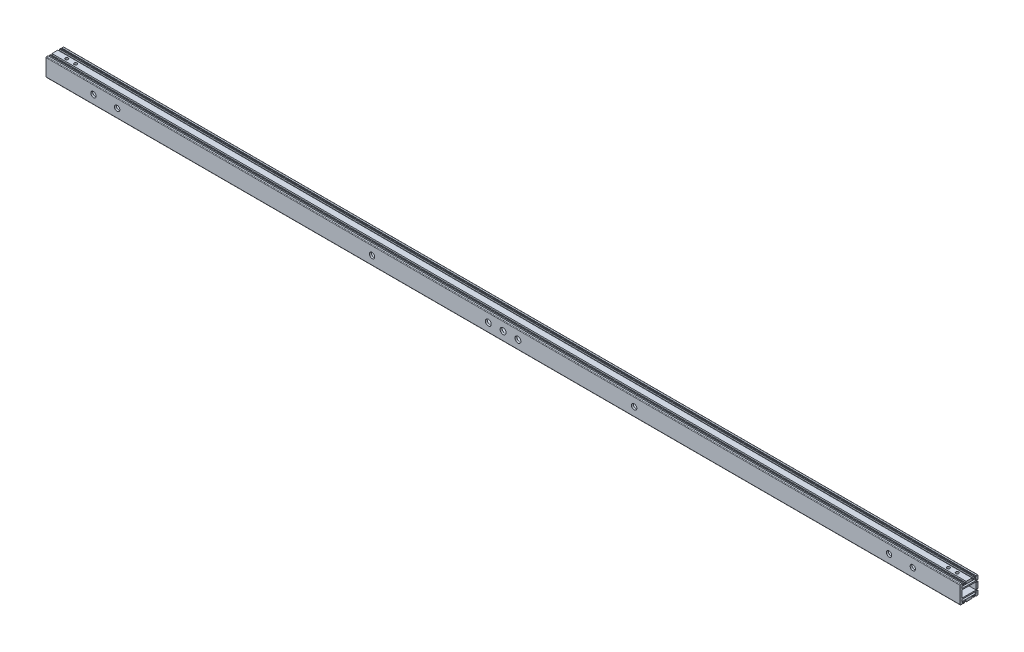
SolidWorks part; units mm, degrees
ref_plane "前视基准面" through (0, 0, 0) normal (0, 0, 1) x (1, 0, 0)
ref_plane "上视基准面" through (0, 0, 0) normal (0, 1, 0) x (1, 0, 0)
ref_plane "右视基准面" through (0, 0, 0) normal (1, 0, 0) x (0, 0, -1)
sketch "草图1" plane through (0, 0, 0) normal (1, 0, 0) x (0, 0, -1)
  line L0 (-15, 15) -> (15, -15) construction
  line L1 (-14, 15) -> (-11.5, 15)
  line L2 (-15, 14) -> (-15, -14)
  line L3 (-14, -15) -> (-11.5, -15)
  line L4 (15, 14) -> (15, 8)
  line L5 (15, 15) -> (-15, -15) construction
  line L6 (-11.5, 15) -> (-11.5, 13.5)
  line L7 (-11.5, 13.5) -> (-11.4, 13.5)
  line L8 (-11, 13.1) -> (-11, 12)
  line L9 (-11, 12) -> (-9.5, 12)
  line L10 (-9.5, 12) -> (-9.5, 15)
  line L11 (-9.5, 15) -> (-8, 15)
  line L12 (-8, 15) -> (-8, 12.5)
  line L13 (-8, 12.5) -> (-5, 12.5)
  line L14 (-5, 12.5) -> (-5, 15)
  line L15 (-5, 15) -> (5, 15)
  line L16 (0, 21.5201) -> (0, -18.309) construction
  line L17 (0, 55) -> (0, -55) construction
  line L18 (5, 12.5) -> (5, 15)
  line L19 (8, 12.5) -> (5, 12.5)
  line L20 (8, 15) -> (8, 12.5)
  line L21 (9.5, 15) -> (8, 15)
  line L22 (9.5, 12) -> (9.5, 15)
  line L23 (11, 12) -> (9.5, 12)
  line L24 (11, 13.1) -> (11, 12)
  line L25 (11.5, 13.5) -> (11.4, 13.5)
  line L26 (11.5, 15) -> (11.5, 13.5)
  line L27 (8, 15) -> (9.5, 15)
  line L28 (11.5, 15) -> (14, 15)
  line L29 (-19.8303, 0) -> (22.13, 0) construction
  line L30 (55, 0) -> (-55, 0) construction
  line L31 (8, -15) -> (9.5, -15)
  line L32 (11.5, -15) -> (11.5, -13.5)
  line L33 (11.5, -13.5) -> (11.4, -13.5)
  line L34 (11, -13.1) -> (11, -12)
  line L35 (11, -12) -> (9.5, -12)
  line L36 (9.5, -12) -> (9.5, -15)
  line L37 (9.5, -15) -> (8, -15)
  line L38 (8, -15) -> (8, -12.5)
  line L39 (8, -12.5) -> (5, -12.5)
  line L40 (5, -12.5) -> (5, -15)
  line L41 (-5, -15) -> (5, -15)
  line L42 (-5, -12.5) -> (-5, -15)
  line L43 (-8, -12.5) -> (-5, -12.5)
  line L44 (-8, -15) -> (-8, -12.5)
  line L45 (-9.5, -15) -> (-8, -15)
  line L46 (-9.5, -12) -> (-9.5, -15)
  line L47 (-11, -12) -> (-9.5, -12)
  line L48 (-11, -13.1) -> (-11, -12)
  line L49 (-11.5, -13.5) -> (-11.4, -13.5)
  line L50 (-11.5, -15) -> (-11.5, -13.5)
  line L51 (-9.5, -15) -> (-8, -15)
  line L52 (-5, -15) -> (5, -15)
  line L53 (8, -15) -> (9.5, -15)
  line L54 (11.5, -15) -> (14, -15)
  line L55 (15, 8) -> (12.5, 8)
  line L56 (12.5, 8) -> (12.5, 5)
  line L57 (12.5, 5) -> (15, 5)
  line L58 (12.5, -5) -> (15, -5)
  line L59 (12.5, -8) -> (12.5, -5)
  line L60 (15, -8) -> (12.5, -8)
  line L61 (15, 5) -> (15, -5)
  line L62 (15, -8) -> (15, -14)
  line L63 (12, -10.5) -> (12, -8.5)
  line L64 (-11.5, 11) -> (11.5, 11)
  line L65 (-12, 10.5) -> (-12, 8.5)
  line L66 (-11.5, 8) -> (11.5, 8)
  line L67 (12, 10.5) -> (12, 8.5)
  line L68 (-11.5, -8) -> (11.5, -8)
  line L69 (-12, -10.5) -> (-12, -8.5)
  line L70 (-11.5, -11) -> (11.5, -11)
  line L72 (-11.75, 6) -> (11.75, 6)
  line L73 (-11.75, 6) -> (-11.75, -6)
  line L74 (-11.75, -6) -> (11.75, -6)
  line L75 (11.75, 6) -> (11.75, -6)
  arc A0 (12, 8.5) -> (11.5, 8) centre (11.5, 8.5) cw
  arc A1 (11.5, 11) -> (12, 10.5) centre (11.5, 10.5) cw
  arc A2 (-11.5, 11) -> (-12, 10.5) centre (-11.5, 10.5) ccw
  arc A3 (-11.5, 8) -> (-12, 8.5) centre (-11.5, 8.5) cw
  arc A4 (-11, -13.1) -> (-11.4, -13.5) centre (-11.4, -13.1) cw
  arc A5 (11.4, -13.5) -> (11, -13.1) centre (11.4, -13.1) cw
  arc A6 (11.4, 13.5) -> (11, 13.1) centre (11.4, 13.1) ccw
  arc A7 (-11, 13.1) -> (-11.4, 13.5) centre (-11.4, 13.1) ccw
  arc A8 (-11.5, -8) -> (-12, -8.5) centre (-11.5, -8.5) ccw
  arc A9 (-11.5, -11) -> (-12, -10.5) centre (-11.5, -10.5) cw
  arc A10 (11.5, -11) -> (12, -10.5) centre (11.5, -10.5) ccw
  arc A11 (12, -8.5) -> (11.5, -8) centre (11.5, -8.5) ccw
  arc A12 (14, 15) -> (15, 14) centre (14, 14) cw
  arc A13 (14, -15) -> (15, -14) centre (14, -14) ccw
  arc A14 (-15, -14) -> (-14, -15) centre (-14, -14) ccw
  arc A15 (-15, 14) -> (-14, 15) centre (-14, 14) cw
  point P69 (12, 11)
  point P72 (-12, 11)
  point P77 (-11, -13.5)
  point P80 (11, -13.5)
  point P83 (11, 13.5)
  point P86 (-11, 13.5)
  point P99 (-12, -11)
  point P100 (12, -11)
  dimension "D17" = 0.5
  dimension "D18" = 0.4
  dimension "D21" = 1
  dimension "D1" = 3.5
  dimension "D2" = 1.5
  dimension "D3" = 0.5
  dimension "D4" = 1.5
  dimension "D5" = 3
  dimension "D6" = 30
  dimension "D7" = 30
  dimension "D8" = 1.5
  dimension "D9" = 2.5
  dimension "D10" = 3
  dimension "D11" = 2.5
  dimension "D12" = 7
  dimension "D13" = 3
  dimension "D14" = 4
  dimension "D15" = 3
  dimension "D16" = 24
  dimension "D19" = 23.5
  dimension "D20" = 12
extrude "凸台-拉伸1" add sketch "草图1" along normal mid plane 1542 contours A15 L2 A14 L3 L50 L49 A4 L48 L47 L46 L45 L44 L43 L42 L41 L40 L39 L38 L31 L36 L35 L34 A5 L33 L32 L54 A13 L62 L60 L59 L58 L61 L57 L56 L55 L4 A12 L28 L26 L25 A6 L24 L23 L22 L21 L20 L19 L18 L15 L14 L13
hole_wizard "M6 螺纹孔1" positions "草图3" profile "草图2" tap size "M6" standard "GB"
sketch "草图3" plane through (0, 0, -15) normal (0, 0, -1) x (-1, 0, 0)
  line L0 (771, 5) -> (771, -5) construction
  line L1 (-771, 15) -> (771, 15) construction
  line L3 (-771, -15) -> (771, -15) construction
  point P0 (751, 0)
  point P6 (736, 0)
  point P8 (-736, 0)
  point P11 (-751, 0)
  dimension "D1" = 20
  dimension "D2" = 15
  dimension "D3" = 15
  dimension "D4" = 15
sketch "草图2" plane through (-751, 0, -15) normal (1, 0, 0) x (0, 1, 0)
  line L0 (0, 0) -> (0, 16.5022)
  line L1 (0, 16.5022) -> (2.5, 15)
  line L2 (2.5, 15) -> (2.5, 0)
  line L5 (2.5, 0) -> (0, 0)
  line L10 (0, 16.5022) -> (-2.5, 15) construction
  line L11 (0, -6.35) -> (0, 107.95) construction
  dimension "螺纹孔钻头直径" = 5
  dimension "螺纹孔钻头深度" = 15
  dimension "导头角度" = 118
cosmetic thread "孔螺蚊线1" parameters "D1"=3.25, "D2"=6
cosmetic thread "孔螺蚊线2" parameters "D1"=3.25, "D2"=6
cosmetic thread "孔螺蚊线3" parameters "D1"=3.25, "D2"=6
cosmetic thread "孔螺蚊线4" parameters "D1"=3.25, "D2"=6
hole_wizard "M6 螺纹孔2" positions "草图5" profile "草图4" tap size "M6" standard "GB"
sketch "草图5" plane through (0, 15, 0) normal (0, 1, 0) x (-1, 0, 0)
  line L0 (-771, 14) -> (-771, 11.5) construction
  line L1 (-771, 15) -> (771, 15) construction
  point P0 (-751, 0)
  point P6 (-736, 0)
  point P9 (736, 0)
  point P12 (751, 0)
  dimension "D1" = 20
  dimension "D2" = 15
sketch "草图4" plane through (751, 15, 0) normal (1, 0, 0) x (0, 0, 1)
  line L0 (0, 0) -> (0, 16.5022)
  line L1 (0, 16.5022) -> (2.5, 15)
  line L2 (2.5, 15) -> (2.5, 0)
  line L5 (2.5, 0) -> (0, 0)
  line L10 (0, 16.5022) -> (-2.5, 15) construction
  line L11 (0, -6.35) -> (0, 107.95) construction
  dimension "螺纹孔钻头直径" = 5
  dimension "螺纹孔钻头深度" = 15
  dimension "导头角度" = 118
cosmetic thread "孔螺蚊线5" parameters "D1"=9, "D2"=6
cosmetic thread "孔螺蚊线6" parameters "D1"=9, "D2"=6
cosmetic thread "孔螺蚊线7" parameters "D1"=9, "D2"=6
cosmetic thread "孔螺蚊线8" parameters "D1"=9, "D2"=6
sketch "草图7" plane through (0, 0, 15) normal (0, 0, 1) x (1, 0, 0)
  line L0 (-771, 0) -> (771, 0) construction
  line L1 (-771, 14) -> (-771, -14) construction
  line L2 (771, 14) -> (771, -14) construction
  circle A0 centre (-651, 0) radius 4.5
  circle A1 centre (-221, 0) radius 4.5
  circle A2 centre (651, 0) radius 4.5
  circle A3 centre (221, 0) radius 4.5
  dimension "D5" = 9
  dimension "D1" = 120
  dimension "D2" = 430
  dimension "D3" = 430
  dimension "D4" = 120
extrude "切除-拉伸1" cut sketch "草图7" against normal through all
sketch "草图8" plane through (0, 0, 15) normal (0, 0, 1) x (1, 0, 0)
  circle A0 centre (0, 0) radius 5
  circle A1 centre (-25, 0) radius 5
  circle A2 centre (25, 0) radius 5
  dimension "D3" = 10
  dimension "D1" = 25
  dimension "D2" = 25
extrude "切除-拉伸2" cut sketch "草图8" against normal blind 15
sketch "草图9" plane through (0, 0, -15) normal (0, 0, -1) x (-1, 0, 0)
  line L0 (-44.5328, 0) -> (94.5328, 0) construction
  line L1 (25, 2.5) -> (25, -2.5) construction
  line L2 (27, 2.5) -> (27, -2.5)
  line L3 (23, 2.5) -> (23, -2.5)
  line L4 (0, 22.9345) -> (0, -23.3146) construction
  line L5 (-25, 2.5) -> (-25, -2.5) construction
  line L6 (-27, 2.5) -> (-27, -2.5)
  line L7 (-23, 2.5) -> (-23, -2.5)
  circle A0 centre (0, 0) radius 3.5
  arc A1 (27, 2.5) -> (23, 2.5) centre (25, 2.5) ccw
  arc A2 (23, -2.5) -> (27, -2.5) centre (25, -2.5) ccw
  arc A3 (-27, 2.5) -> (-23, 2.5) centre (-25, 2.5) cw
  arc A4 (-23, -2.5) -> (-27, -2.5) centre (-25, -2.5) cw
  point P7 (25, 0)
  point P16 (-25, 0)
  dimension "D1" = 7
  dimension "D3" = 5
  dimension "D2" = 4
  dimension "D4" = 50
extrude "切除-拉伸3" cut sketch "草图9" against normal blind 15
hole_wizard "M6 螺纹孔3" positions "草图11" profile "草图10" tap size "M6" standard "GB"
sketch "草图11" plane through (0, 0, -15) normal (0, 0, -1) x (-1, 0, 0)
  line L0 (-771, -8) -> (-771, -14) construction
  line L1 (771, -8) -> (771, -14) construction
  line L2 (-771, -15) -> (771, -15) construction
  point P0 (411, 0)
  point P1 (351, 0)
  point P3 (321, 0)
  point P5 (261, 0)
  point P7 (-261, 0)
  point P9 (-321, 0)
  point P11 (-351, 0)
  point P13 (-411, 0)
  dimension "D1" = 60
  dimension "D2" = 60
  dimension "D3" = 360
  dimension "D4" = 450
  dimension "D5" = 60
  dimension "D6" = 60
  dimension "D7" = 360
  dimension "D8" = 450
  dimension "D9" = 15
sketch "草图10" plane through (-411, 0, -15) normal (1, 0, 0) x (0, 1, 0)
  line L0 (0, 0) -> (0, 16.5022)
  line L1 (0, 16.5022) -> (2.5, 15)
  line L2 (2.5, 15) -> (2.5, 0)
  line L5 (2.5, 0) -> (0, 0)
  line L10 (0, 16.5022) -> (-2.5, 15) construction
  line L11 (0, -6.35) -> (0, 107.95) construction
  dimension "螺纹孔钻头直径" = 5
  dimension "螺纹孔钻头深度" = 15
  dimension "导头角度" = 118
cosmetic thread "孔螺蚊线9" parameters "D1"=3.25, "D2"=6
cosmetic thread "孔螺蚊线10" parameters "D1"=3.25, "D2"=6
cosmetic thread "孔螺蚊线11" parameters "D1"=3.25, "D2"=6
cosmetic thread "孔螺蚊线12" parameters "D1"=3.25, "D2"=6
cosmetic thread "孔螺蚊线13" parameters "D1"=3.25, "D2"=6
cosmetic thread "孔螺蚊线14" parameters "D1"=3.25, "D2"=6
cosmetic thread "孔螺蚊线15" parameters "D1"=3.25, "D2"=6
cosmetic thread "孔螺蚊线16" parameters "D1"=3.25, "D2"=6
hole_wizard "M6 螺纹孔4" positions "草图13" profile "草图12" tap size "M6" standard "GB"
sketch "草图13" plane through (0, 0, -15) normal (0, 0, -1) x (-1, 0, 0)
  line L0 (-771, -15) -> (771, -15) construction
  line L1 (-771, -8) -> (-771, -14) construction
  line L2 (771, -8) -> (771, -14) construction
  point P0 (691, 0)
  point P1 (-691, 0)
  dimension "D1" = 15
  dimension "D2" = 80
  dimension "D3" = 15
  dimension "D4" = 80
sketch "草图12" plane through (-691, 0, -15) normal (1, 0, 0) x (0, 1, 0)
  line L0 (0, 0) -> (0, 16.5022)
  line L1 (0, 16.5022) -> (2.5, 15)
  line L2 (2.5, 15) -> (2.5, 0)
  line L5 (2.5, 0) -> (0, 0)
  line L10 (0, 16.5022) -> (-2.5, 15) construction
  line L11 (0, -6.35) -> (0, 107.95) construction
  dimension "螺纹孔钻头直径" = 5
  dimension "螺纹孔钻头深度" = 15
  dimension "导头角度" = 118
cosmetic thread "孔螺蚊线17" parameters "D1"=3.25, "D2"=6
cosmetic thread "孔螺蚊线18" parameters "D1"=3.25, "D2"=6
sketch "草图14" plane through (0, 0, -15) normal (0, 0, -1) x (-1, 0, 0)
  circle A0 centre (691, 0) radius 4.5
  circle A1 centre (-691, 0) radius 4.5
  dimension "D1" = 9
extrude "切除-拉伸4" cut sketch "草图14" against normal through all
